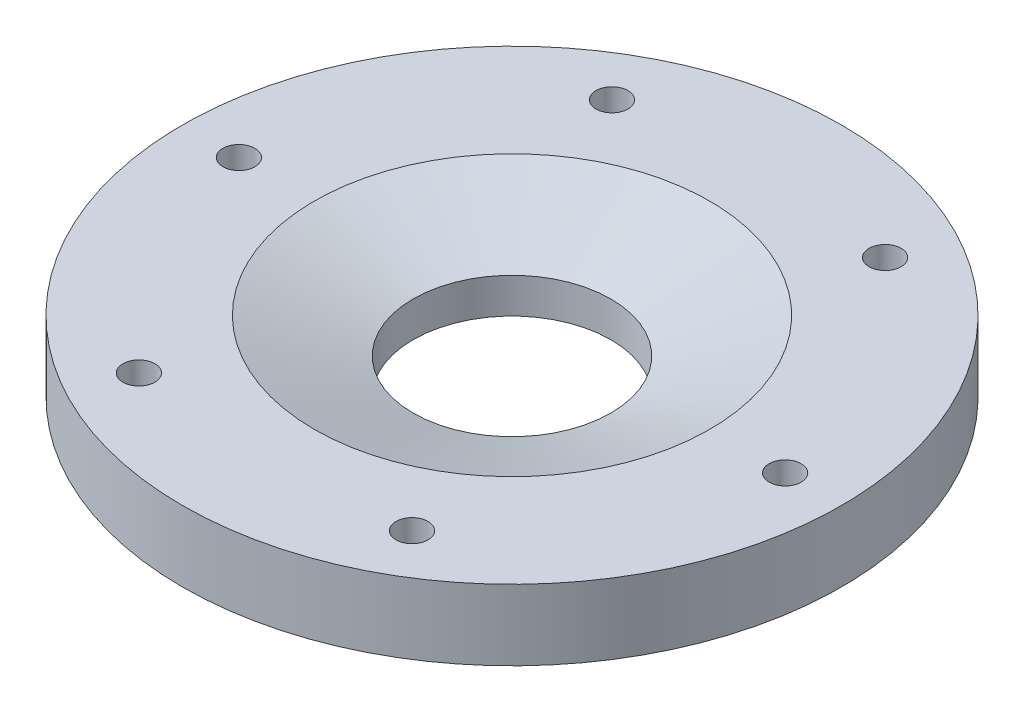
SolidWorks part; units mm, degrees
ref_plane "Płaszczyzna przednia" through (0, 0, 0) normal (0, 0, 1) x (1, 0, 0)
ref_plane "Płaszczyzna górna" through (0, 0, 0) normal (0, 1, 0) x (1, 0, 0)
ref_plane "Płaszczyzna prawa" through (0, 0, 0) normal (1, 0, 0) x (0, 0, -1)
sketch "Szkic1" plane through (0, 0, 0) normal (0, 0, 1) x (1, 0, 0)
  line L0 (0, 48.9807) -> (0, -9.5073) construction
  line L1 (-70, 9.1031) -> (-70, -5.8969)
  line L3 (-70, 1.6031) -> (0, 1.6031) construction
  line L4 (-21, 1.6031) -> (-21, -5.8969)
  line L5 (-42, 9.1031) -> (-21, 1.6031)
  line L6 (-70, 9.1031) -> (-42, 9.1031)
  line L7 (-70, -5.8969) -> (-21, -5.8969)
  dimension "D1" = 70
  dimension "D2" = 42
  dimension "D3" = 15
  dimension "D4" = 21
revolve "Obrót1" add sketch "Szkic1" angle 360 about L0
hole_wizard "Otwór gwintowany M81" positions "Szkic2" profile "Szkic3" tap size "M8" standard "ISO" end condition through all
sketch "Szkic2" plane through (0, 9.1031, 0) normal (0, 1, 0) x (1, 0, 0)
  point P0 (-58.0152, 0)
  point P1 (-29.0076, 50.2426)
  point P2 (29.0076, 50.2426)
  point P3 (58.0152, 0)
  point P4 (29.0076, -50.2426)
  point P5 (-29.0076, -50.2426)
sketch "Szkic3" plane through (-58.0152, 9.1031, 0) normal (1, 0, 0) x (0, 0, 1)
  line L0 (0, 0) -> (0, 15)
  line L1 (0, 15) -> (3.4, 15)
  line L2 (3.4, 15) -> (3.4, 0)
  line L5 (3.4, 0) -> (0, 0)
  line L11 (0, -6.35) -> (0, 107.95) construction
  dimension "Średnica otworu gwintowanego na wylot" = 6.8
  dimension "Głębokość otworu gwintowanego na wylot" = 15
cosmetic thread "Gwint otworu1" parameters "D1"=15, "D2"=8
cosmetic thread "Gwint otworu2" parameters "D1"=15, "D2"=8
cosmetic thread "Gwint otworu3" parameters "D1"=15, "D2"=8
cosmetic thread "Gwint otworu4" parameters "D1"=15, "D2"=8
cosmetic thread "Gwint otworu5" parameters "D1"=15, "D2"=8
cosmetic thread "Gwint otworu6" parameters "D1"=15, "D2"=8
